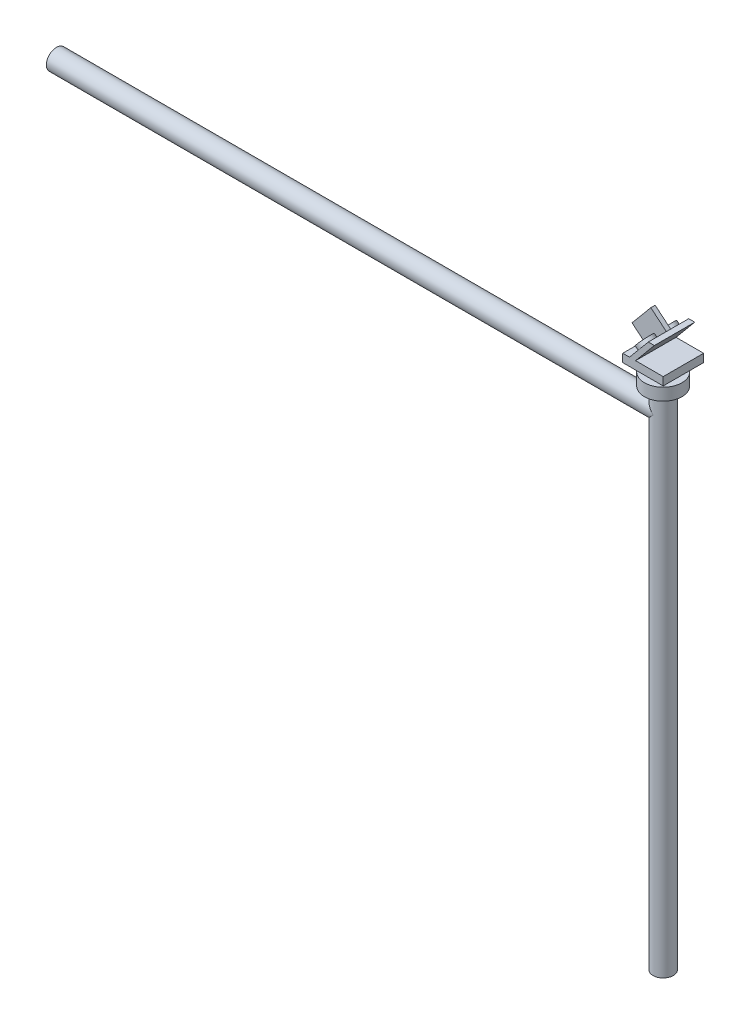
SolidWorks part; units mm, degrees
ref_plane "Front Plane" through (0, 0, 0) normal (0, 0, 1) x (1, 0, 0)
ref_plane "Top Plane" through (0, 0, 0) normal (0, 1, 0) x (1, 0, 0)
ref_plane "Right Plane" through (0, 0, 0) normal (1, 0, 0) x (0, 0, -1)
sketch "Sketch1" plane through (0, 0, 0) normal (0, 1, 0) x (1, 0, 0)
  circle A0 centre (0, 0) radius 2.5
ref_plane "Plane1" through (0, 0, 0) normal (0, 0, 1) x (1, 0, 0)
sketch "Sketch2" plane through (0, 0, 0) normal (0, 0, 1) x (1, 0, 0)
  line L0 (0, 0) -> (0, 120)
  line L1 (0, 120) -> (-150, 120)
  dimension "D1" = 150
  dimension "D2" = 120
sweep "Sweep1" add profiles "Sketch1" path "Sketch2"
ref_plane "Plane3" through (0, 130, 0) normal (0, 1, 0) x (1, 0, 0)
sketch "Sketch3" plane through (0, 130, 0) normal (0, 1, 0) x (1, 0, 0)
  circle A0 centre (0, 0) radius 2.5
extrude "Boss-Extrude1" add sketch "Sketch3" against normal blind 10
sketch "Sketch4" plane through (0, 130, 0) normal (0, 1, 0) x (1, 0, 0)
  circle A0 centre (0, 0) radius 4.6325
  circle A1 centre (0, 0) radius 2.5
extrude "Boss-Extrude2" add sketch "Sketch4" against normal blind 3 from offset 2 separate body offset against normal yes
sketch "Sketch5" plane through (0, 130, 0) normal (0, 1, 0) x (1, 0, 0)
  line L1 (-5, 5) -> (5, 5)
  line L2 (-5, 5) -> (-5, -5)
  line L3 (-5, -5) -> (5, -5)
  line L4 (5, 5) -> (5, -5)
  line L5 (-5, 5) -> (5, -5) construction
  line L6 (-5, -5) -> (5, 5) construction
  point P0 (0, 0)
  dimension "D1" = 10
  dimension "D2" = 10
extrude "Boss-Extrude3" add sketch "Sketch5" along normal blind 2
sketch "Sketch6" plane through (0, 0, 5) normal (0, 0, 1) x (1, 0, 0)
  line L0 (-3.3268, 132) -> (1.3165, 137.5666)
  line L1 (-5, 132) -> (5, 132) construction
  line L2 (1.3165, 137.5666) -> (2.8165, 137.5666)
  line L3 (2.8165, 137.5666) -> (-1.8268, 132)
  line L4 (-3.3268, 132) -> (-1.8268, 132)
  dimension "D1" = 1.5
extrude "Boss-Extrude4" add sketch "Sketch6" against normal through all
sketch "Sketch7" plane through (-66.8912, 55.7966, 0) normal (-0.7679, 0.6406, 0) x (0, 0, 1)
  line L0 (0, 99.2339) -> (0, 106.483) construction
  line L1 (-5, 99.2339) -> (5, 99.2339) construction
  line L2 (-5, 106.483) -> (5, 106.483) construction
  line L4 (-0.5349, 106.483) -> (0.5349, 106.483)
  line L5 (-0.5349, 106.483) -> (-0.5349, 99.2339)
  line L6 (-0.5349, 99.2339) -> (0.5349, 99.2339)
  line L7 (0.5349, 106.483) -> (0.5349, 99.2339)
  line L8 (-0.5349, 106.483) -> (0.5349, 99.2339) construction
  line L9 (-0.5349, 99.2339) -> (0.5349, 106.483) construction
  point P6 (0, 102.8584)
extrude "Boss-Extrude5" add sketch "Sketch7" along normal blind 5
sketch "Sketch9" plane through (-66.8912, 55.7966, 0) normal (-0.7679, 0.6406, 0) x (0, 0, 1)
  line L0 (-5, 102.8584) -> (5, 102.8584) construction
  line L1 (-5, 106.483) -> (-5, 99.2339) construction
  line L2 (5, 106.483) -> (5, 99.2339) construction
  line L3 (0, 106.483) -> (0, 99.2339) construction
  line L4 (0.5349, 106.483) -> (-0.5349, 106.483) construction
  line L5 (-0.5349, 99.2339) -> (0.5349, 99.2339) construction
  line L6 (-0.5349, 106.483) -> (-5, 106.483) construction
  circle A0 centre (-2.7675, 102.8584) radius 2
extrude "Boss-Extrude7" add sketch "Sketch9" along normal blind 1 separate body
sketch "Sketch10" plane through (-66.8912, 55.7966, 0) normal (-0.7679, 0.6406, 0) x (0, 0, 1)
  line L0 (0.5349, 106.483) -> (5, 106.483) construction
  line L1 (5, 106.483) -> (5, 99.2339) construction
  circle A0 centre (2.7675, 102.8584) radius 2
extrude "Boss-Extrude8" add sketch "Sketch10" along normal blind 1 separate body
